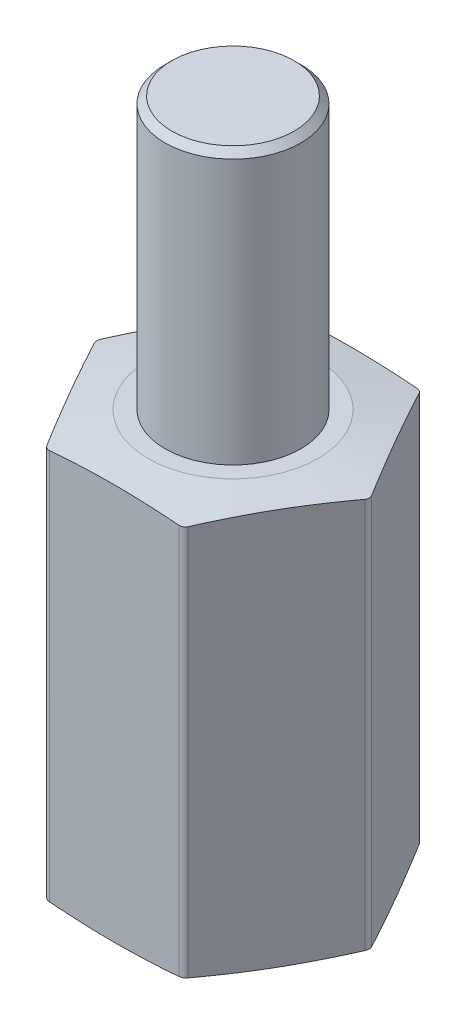
SolidWorks part; units mm, degrees
material "6063-O，挤压棒材(SS)"
ref_plane "前视基准面" through (0, 0, 0) normal (0, 0, 1) x (1, 0, 0)
ref_plane "上视基准面" through (0, 0, 0) normal (0, 1, 0) x (1, 0, 0)
ref_plane "右视基准面" through (0, 0, 0) normal (1, 0, 0) x (0, 0, -1)
sketch "草图1" plane through (0, 0, 0) normal (0, 1, 0) x (1, 0, 0)
  line L1 (4.0415, 0) -> (2.0207, 3.5)
  line L2 (2.0207, 3.5) -> (-2.0207, 3.5)
  line L3 (-2.0207, 3.5) -> (-4.0415, 0)
  line L4 (-4.0415, 0) -> (-2.0207, -3.5)
  line L5 (-2.0207, -3.5) -> (2.0207, -3.5)
  line L6 (2.0207, -3.5) -> (4.0415, 0)
  circle A0 centre (0, 0) radius 3.5 construction
  dimension "六角对边距离" = 7
extrude "凸台-拉伸1" add sketch "草图1" along normal mid plane 12
fillet "圆角1" radius 0.2 6 edges at (2.0207, 0, -3.5) (-4.0415, 0, 0) (-2.0207, 0, -3.5) (-2.0207, 0, 3.5) (4.0415, 0, 0) (2.0207, 0, 3.5)
sketch "草图3" plane through (0, -6, 0) normal (0, 1, 0) x (1, 0, 0)
  circle A0 centre (0, 0) radius 2
  dimension "螺纹公称尺寸" = 4
extrude "切除-拉伸1" cut sketch "草图3" along normal blind 8
sketch "草图4" plane through (0, 0, 0) normal (0, 0, 1) x (1, 0, 0)
  line L0 (-2, 6) -> (-4.0105, 6) construction
  line L1 (-1.9053, 6) -> (1.9053, 6) construction
  line L2 (-4.0105, 6) -> (-4.0105, 5.75)
  line L4 (-4.0105, 6) -> (-4.0105, -6) construction
  line L5 (-2, 0.161) -> (-2, 8.9742) construction
  line L9 (-4.0105, 5.75) -> (-2.5, 6)
  line L10 (-2.5, 6) -> (-4.0105, 6)
  line L11 (0, 0) -> (0, 6) construction
  dimension "D1" = 0.25
  dimension "D2" = 0.5
revolve "切除-旋转1" cut sketch "草图4" angle 360 about L11
mirror "镜向1" about plane through (0, 0, 0) normal (0, 1, 0) of "切除-旋转1"
sketch "草图5" plane through (0, 6, 0) normal (0, 1, 0) x (1, 0, 0)
  circle A0 centre (0, 0) radius 2
  circle A1 centre (0, 0) radius 2 construction
extrude "凸台-拉伸2" add sketch "草图5" along normal blind 8
chamfer "倒角1" distance 0.2 angle 45 1 edges at (0, 14, 2)
other "冻结***"
